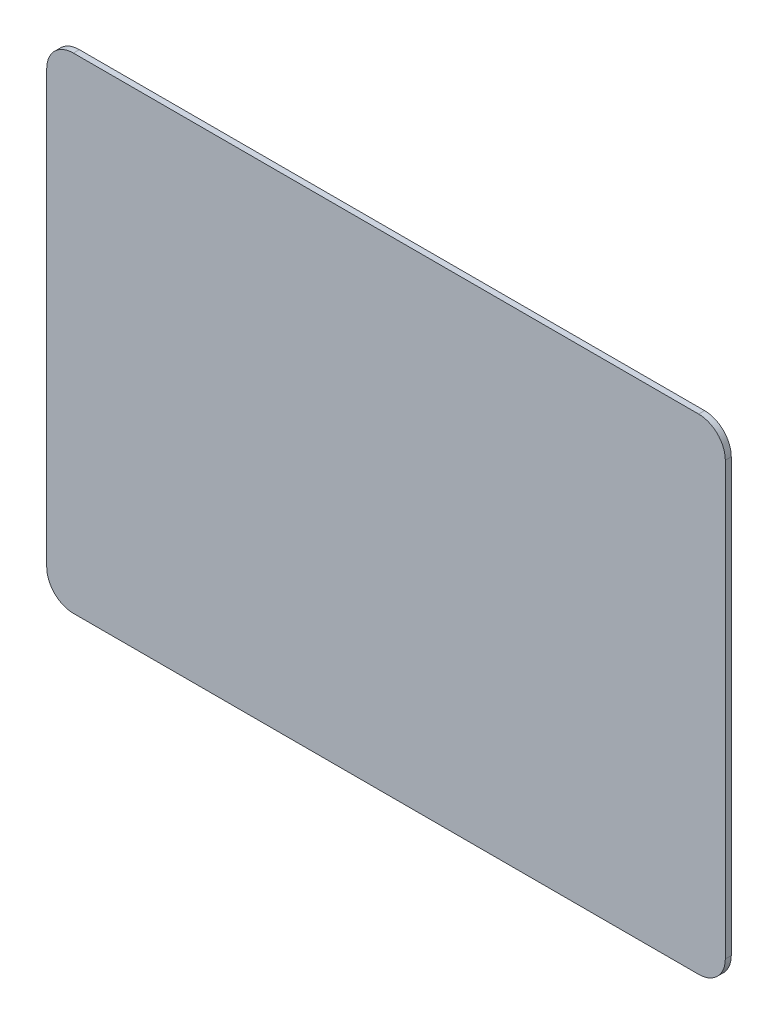
SolidWorks part; units mm, degrees
ref_plane "Front Plane" through (0, 0, 0) normal (0, 0, 1) x (1, 0, 0)
ref_plane "Top Plane" through (0, 0, 0) normal (0, 1, 0) x (1, 0, 0)
ref_plane "Right Plane" through (0, 0, 0) normal (1, 0, 0) x (0, 0, -1)
sketch "Sketch1" plane through (0, 0, 0) normal (0, 0, 1) x (1, 0, 0)
  line L0 (280.9201, 7.8322) -> (280.9201, -197.1458) construction
  line L1 (-41.4059, 34.7562) -> (292.0961, 34.7562)
  line L2 (-55.6299, 20.5322) -> (-55.6299, -209.8458)
  line L3 (-41.4059, -224.0698) -> (292.0961, -224.0698)
  line L4 (306.3201, 20.5322) -> (306.3201, -209.8458)
  arc A0 (-41.4059, 34.7562) -> (-55.6299, 20.5322) centre (-41.4059, 20.5322) ccw
  arc A1 (-55.6299, -209.8458) -> (-41.4059, -224.0698) centre (-41.4059, -209.8458) ccw
  arc A2 (292.0961, -224.0698) -> (306.3201, -209.8458) centre (292.0961, -209.8458) ccw
  arc A3 (306.3201, 20.5322) -> (292.0961, 34.7562) centre (292.0961, 20.5322) ccw
  point P6 (-55.6299, 34.7562)
  point P9 (-55.6299, -224.0698)
  point P14 (306.3201, 34.7562)
  point P15 (306.3201, -94.6568)
  point P18 (280.9201, -94.6568)
  dimension "D3" = 14.224
  dimension "D4" = 14.224
  dimension "D1" = 361.95
  dimension "D2" = 258.826
extrude "Boss-Extrude1" add sketch "Sketch1" against normal blind 3.175
